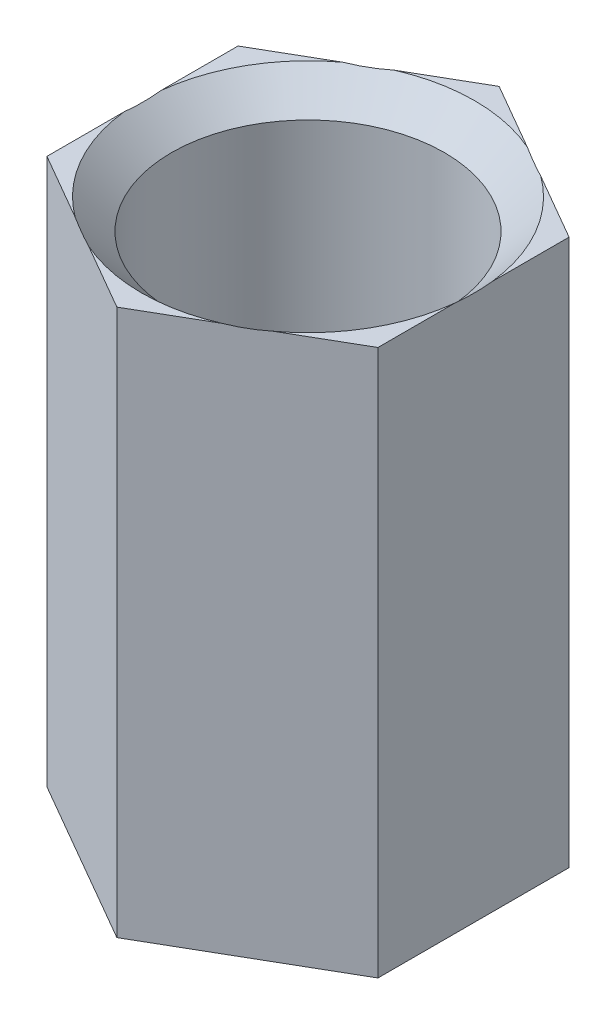
SolidWorks part; units mm, degrees
ref_plane "Front Plane" through (0, 0, 0) normal (0, 0, 1) x (1, 0, 0)
ref_plane "Top Plane" through (0, 0, 0) normal (0, 1, 0) x (1, 0, 0)
ref_plane "Right Plane" through (0, 0, 0) normal (1, 0, 0) x (0, 0, -1)
sketch "Sketch1" plane through (0, 0, 0) normal (0, 1, 0) x (1, 0, 0)
  line L3 (0, 0) -> (0, 1.5)
  line L5 (0, 0) -> (1.299, 0.75)
  line L6 (0, 0) -> (1.299, -0.75)
  line L7 (0, 0) -> (0, -1.5)
  line L9 (0, 0) -> (-1.299, -0.75)
  line L13 (0, 0) -> (-1.299, 0.75)
  line L15 (0, 1.5) -> (0, 2.0597)
  line L16 (1.299, 0.75) -> (1.9943, 1.1514)
  line L17 (0, 0) -> (0.75, 1.299)
  line L18 (0, 1.75) -> (1.5155, 0.875)
  line L19 (1.299, -0.75) -> (1.5155, -0.875)
  line L20 (1.5155, -0.875) -> (1.5155, 0.875)
  line L21 (0, -1.5) -> (0, -1.75)
  line L22 (0, -1.75) -> (1.5155, -0.875)
  line L23 (-1.299, -0.75) -> (-1.5155, -0.875)
  line L24 (-1.5155, -0.875) -> (0, -1.75)
  line L25 (-1.299, 0.75) -> (-1.5155, 0.875)
  line L26 (-1.5155, 0.875) -> (-1.5155, -0.875)
  line L27 (-1.5155, 0.875) -> (0, 1.75)
  circle A0 centre (0, 0) radius 1.75
  circle A2 centre (0, 0) radius 1.5
  point P11 (0, 0)
  point P14 (0, 0)
  dimension "D1" = 6
  dimension "D2" = 30
extrude "Boss-Extrude2" add sketch "Sketch1" along normal blind 5 contours A2 L25 L26 L23 | L13 A2 L9 | A2 L23 L24 L21 | L9 A2 L7 | L7 A2 L6 | L6 A2 L5 | L5 A2 L17 | L17 A2 L3 | L3 A2 L13 | A2 L15 L27 L25 | A2 L16 L18 L15 | A2 L19 L20 L16 | A2 L21 L22 L19
sketch "Sketch3" plane through (0, 5, 0) normal (0, 1, 0) x (1, 0, 0)
  circle A0 centre (0, 0) radius 1.5
hole_wizard "M3 Tapped Hole1" positions "Sketch4" profile "Sketch5" tap size "M3" standard "ISO" end condition through all
sketch "Sketch4" plane through (0, 5, 0) normal (0, 1, 0) x (1, 0, 0)
  point P0 (0, 0)
cosmetic thread "Hole Thread1" parameters "D2"=3
sketch "Sketch5" plane through (0, 5, 0) normal (1, 0, 0) x (0, 0, 1)
  line L0 (0, 0) -> (0, 5)
  line L1 (0, 5) -> (1.25, 5)
  line L2 (1.25, 5) -> (1.25, 0.275)
  line L3 (1.25, 0.275) -> (1.525, 0)
  line L5 (1.525, 0) -> (0, 0)
  line L6 (-1.25, 0.275) -> (-1.525, 0) construction
  line L11 (0, -6.35) -> (0, 107.95) construction
  dimension "Thru Tap Drill Dia." = 2.5
  dimension "Thru Tap Drill Depth" = 5
  dimension "Near C'Sink Dia." = 3.05
  dimension "Near C'Sink Angle" = 90
